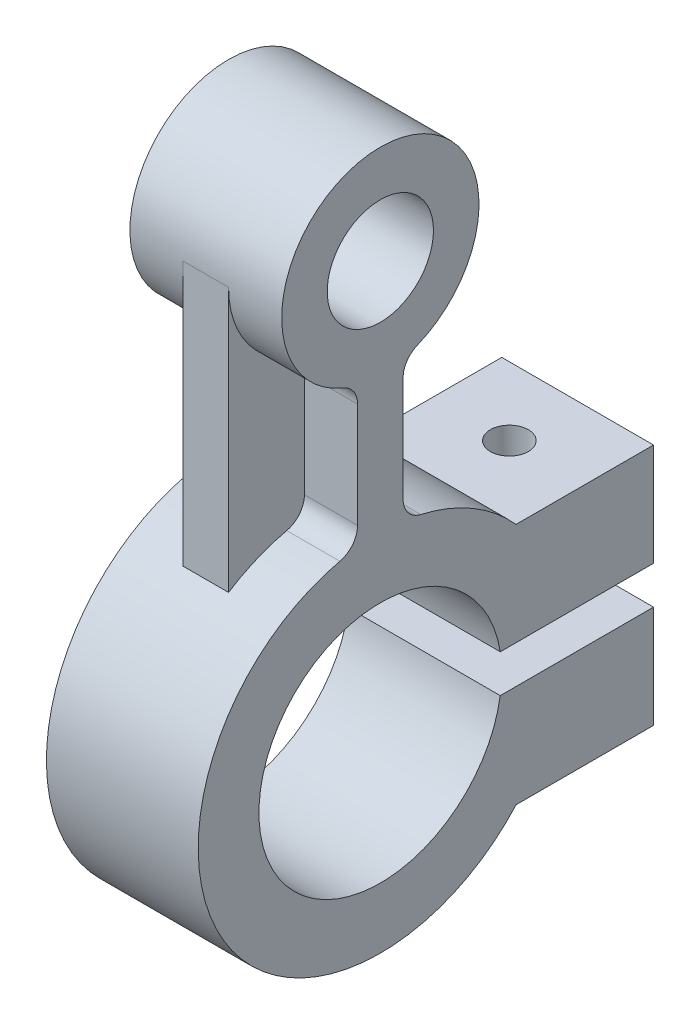
SolidWorks part; units mm, degrees
ref_plane "Front Plane" through (0, 0, 0) normal (1, 0, 0) x (0, 1, 0)
ref_plane "Top Plane" through (0, 0, 0) normal (0, 0, 1) x (0, 1, 0)
ref_plane "Right Plane" through (0, 0, 0) normal (0, 1, 0) x (-1, 0, 0)
sketch "Sketch1" plane through (0, 0, 0) normal (1, 0, 0) x (0, 1, 0)
  line L0 (0, 0) -> (55, 0) construction
  line L1 (26.3249, 3) -> (40.1676, 3)
  line L2 (26.3249, -3) -> (40.1676, -3)
  line L3 (-16, -36) -> (-2.5, -36)
  line L4 (-16, -36) -> (-16, -17.8885)
  line L5 (16, -36) -> (16, -17.8885)
  line L7 (2.5, -36) -> (2.5, -15.8035)
  line L9 (-2.5, -15.8035) -> (-2.5, -36)
  line L10 (2.5, -36) -> (16, -36)
  line L11 (0, 0) -> (0, -9.1147) construction
  arc A0 (2.5, -15.8035) -> (-2.5, -15.8035) centre (0, 0) ccw
  arc A1 (23.3999, 5.3333) -> (-16, -17.8885) centre (0, 0) ccw
  arc A2 (42.9487, -4.875) -> (42.9487, 4.875) centre (55, 0) ccw
  circle A3 centre (55, 0) radius 7
  arc A4 (26.3249, -3) -> (23.3999, -5.3333) centre (26.3249, -6) ccw
  arc A5 (40.1676, -3) -> (42.9487, -4.875) centre (40.1676, -6) cw
  arc A6 (40.1676, 3) -> (42.9487, 4.875) centre (40.1676, 6) ccw
  arc A7 (26.3249, 3) -> (23.3999, 5.3333) centre (26.3249, 6) cw
  arc A8 (16, -17.8885) -> (23.3999, -5.3333) centre (0, 0) ccw
  point P25 (0, -36)
  dimension "D1" = 32
  dimension "D2" = 48
  dimension "D3" = 14
  dimension "D4" = 26
  dimension "D7" = 3
  dimension "D5" = 55
  dimension "D6" = 6
  dimension "D8" = 32
  dimension "D9" = 36
  dimension "D10" = 5
extrude "Boss-Extrude1" add sketch "Sketch1" along normal mid plane 20
sketch "Sketch2" plane through (0, 0, 0) normal (1, 0, 0) x (0, 1, 0)
  line L0 (55, 13) -> (20.1742, 13)
  arc A0 (42.9487, -4.875) -> (42.9487, 4.875) centre (55, 0) ccw construction
  arc A1 (23.3999, 5.3333) -> (-16, -17.8885) centre (0, 0) ccw construction
rib "Rib1" sketch "Sketch2" sketch "Sketch2" thickness 6 extrusion direction parallel to sketch draft on no parameters "D1"=6
sketch "Sketch3" plane through (0, 16, 0) normal (0, 1, 0) x (-1, 0, 0)
  line L0 (-10, -36) -> (-10, -17.8885) construction
  line L1 (-10, -36) -> (10, -36) construction
  circle A0 centre (0, -27) radius 2.5
  dimension "D1" = 5
  dimension "D2" = 10
  dimension "D3" = 9
extrude "Cut-Extrude1" cut sketch "Sketch3" against normal through all
